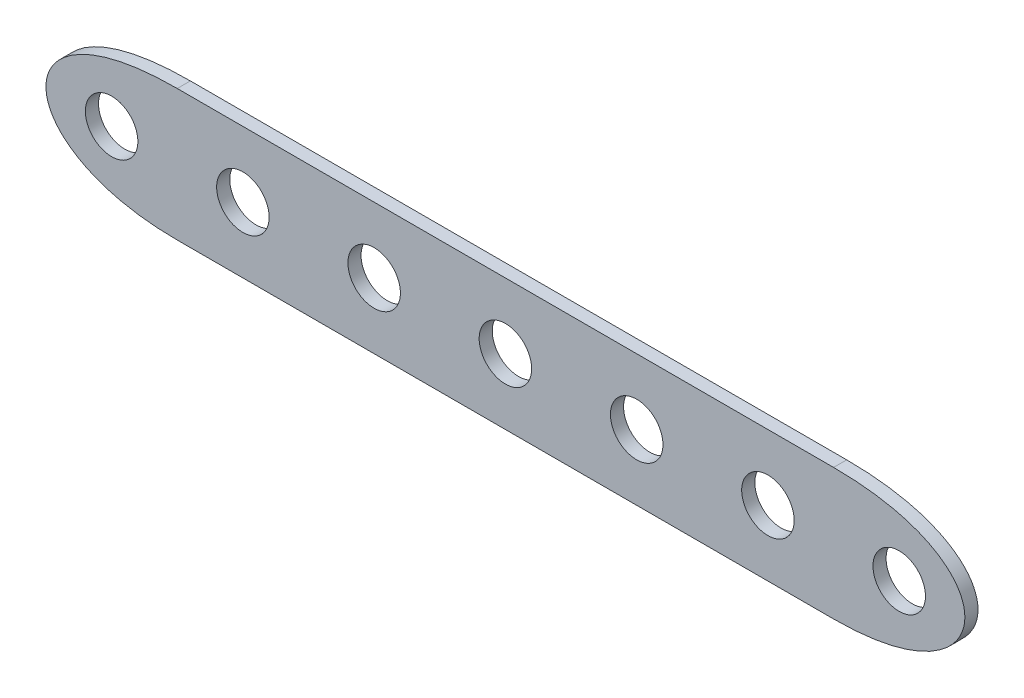
SolidWorks part; units mm, degrees
ref_plane "Спереди" through (0, 0, 0) normal (0, 0, 1) x (1, 0, 0)
ref_plane "Сверху" through (0, 0, 0) normal (0, 1, 0) x (1, 0, 0)
ref_plane "Справа" through (0, 0, 0) normal (1, 0, 0) x (0, 0, -1)
sketch "Эскиз3" plane through (0, 0, 0) normal (0, 0, 1) x (1, 0, 0)
  line L0 (10, 0) -> (60, 0)
  line L1 (60, -10) -> (10, -10)
  circle A0 centre (5, -5) radius 2
  circle A1 centre (65, -5) radius 2
  circle A2 centre (15, -5) radius 2
  circle A3 centre (25, -5) radius 2
  circle A4 centre (35, -5) radius 2
  circle A5 centre (45, -5) radius 2
  circle A6 centre (55, -5) radius 2
  spline S0 degree 3 poles (60, 0) (73.7437, 0) (72.923, -10) (60, -10) knots 0 0 0 0 1 1 1 1
  spline S1 degree 3 poles (10, 0) (-3.7437, 0) (-2.923, -10) (10, -10) knots 0 0 0 0 1 1 1 1
  point P3 (70, -5)
  point P5 (0, -5)
  dimension "D1" = 70
extrude "Бобышка-Вытянуть1" add sketch "Эскиз3" along normal blind 1
